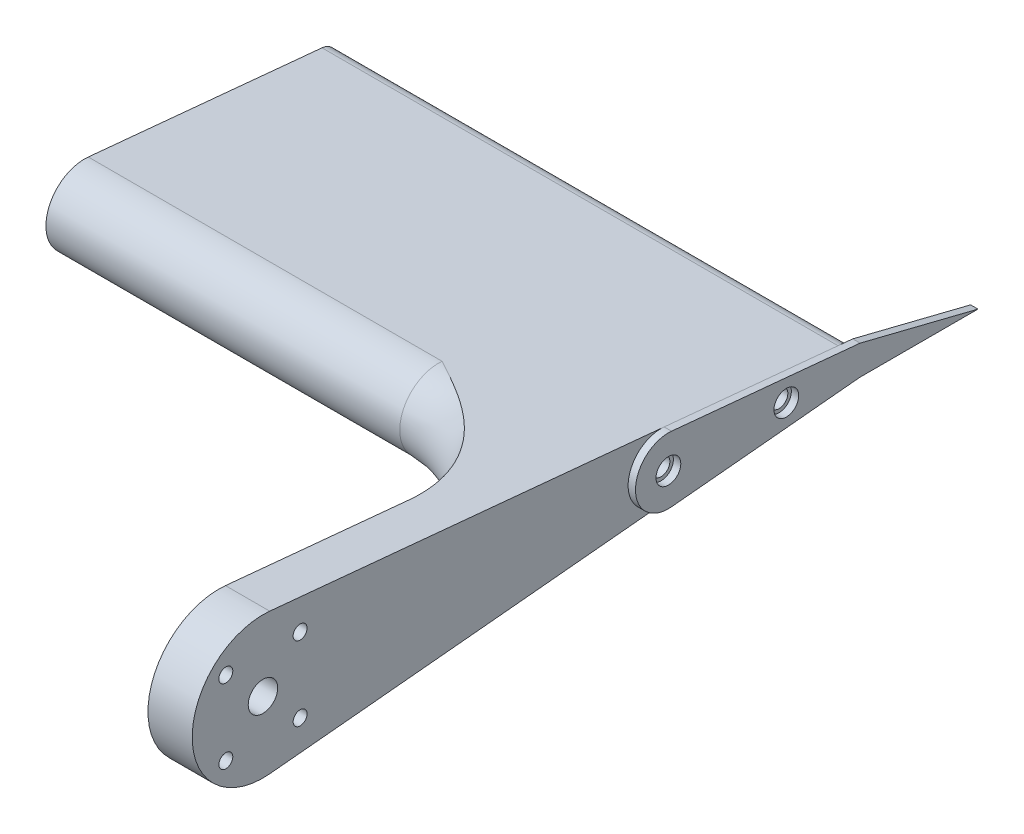
SolidWorks part; units mm, degrees
material "PLA/ABS"
ref_plane "Front Plane" through (0, 0, 0) normal (0, 0, 1) x (1, 0, 0)
ref_plane "Top Plane" through (0, 0, 0) normal (0, 1, 0) x (1, 0, 0)
ref_plane "Right Plane" through (0, 0, 0) normal (1, 0, 0) x (0, 0, -1)
other "Bounding Box"
ref_plane "Default Plane" through (-8.9266, -12.7485, 0) normal (-0.1736, 0.9848, 0) x (0.9848, 0.1736, 0)
sketch "Sketch1" plane through (0, 0, 0) normal (1, 0, 0) x (0, 0, -1)
  line L0 (1.4495, 15.1709) -> (123.8394, 3.477)
  line L1 (-8, 8) -> (8, 8) construction
  line L2 (-8, 8) -> (-8, -8) construction
  line L3 (-8, -8) -> (8, -8) construction
  line L4 (8, 8) -> (8, -8) construction
  line L5 (-8, 8) -> (8, -8) construction
  line L6 (-8, -8) -> (8, 8) construction
  line L7 (1.4495, -15.1709) -> (123.8394, -3.477)
  line L8 (0, 0) -> (152.4, 0) construction
  line L11 (127, -3.175) -> (127, 3.175) construction
  line L12 (127, 3.175) -> (152.4, -3.175) construction
  line L13 (152.4, -3.175) -> (127, -3.175) construction
  line L14 (152.4, -3.175) -> (152.4, 0) construction
  line L15 (123.8394, -3.477) -> (127, -3.175) construction
  line L16 (123.8394, 3.477) -> (127, 3.175) construction
  circle A0 centre (0, 0) radius 3.175
  circle A1 centre (-8, 8) radius 1.5
  circle A2 centre (8, 8) radius 1.5
  circle A3 centre (8, -8) radius 1.5
  circle A4 centre (-8, -8) radius 1.5
  arc A5 (1.4495, 15.1709) -> (1.4495, -15.1709) centre (0, 0) ccw
  arc A8 (123.8394, 3.477) -> (123.8394, -3.477) centre (123.5072, 0) cw
  point P13 (127, 0)
  point P20 (127, 0)
  point P22 (127, 0)
  dimension "D2" = 3
  dimension "D3" = 6.35
  dimension "D10" = 15.24
  dimension "D1" = 16
  dimension "D4" = 152.4
  dimension "D5" = 6.35
  dimension "D6" = 25.4
extrude "Boss-Extrude1" add sketch "Sketch1" along normal mid plane 9.525
sketch "Sketch3" plane through (-4.7625, 0, 0) normal (-1, 0, 0) x (0, 0, 1)
  line L0 (-123.8394, 3.477) -> (-1.4495, 15.1709) construction
  line L1 (-123.5072, 0) -> (-72.7072, 0) construction
  line L2 (-1.4495, 15.1709) -> (-123.8394, 3.477)
  line L3 (-123.8394, -3.477) -> (-1.4495, -15.1709)
  line L4 (-73.499, 8.2868) -> (-123.8394, 3.477)
  line L5 (-123.8394, -3.477) -> (-73.499, -8.2868)
  arc A0 (-73.499, 8.2868) -> (-73.499, -8.2868) centre (-72.7072, 0) cw
  arc A2 (-1.4495, -15.1709) -> (-1.4495, 15.1709) centre (0, 0) ccw
  arc A3 (-123.8394, 3.477) -> (-123.8394, -3.477) centre (-123.5072, 0) ccw
  arc A5 (-123.8394, 3.477) -> (-123.8394, -3.477) centre (-123.5072, 0) ccw
  point P5 (-65.2565, 9.0744)
  dimension "D2" = 50.8
  dimension "D1" = 0
extrude "Boss-Extrude2" add sketch "Sketch3" along normal blind 101.6
sketch "Sketch4" plane through (4.7625, 0, 0) normal (1, 0, 0) x (0, 0, -1)
  line L0 (0, 0) -> (152.4, 0) construction
  line L1 (1.4495, -15.1709) -> (123.8394, -3.477) construction
  line L2 (1.4495, 15.1709) -> (123.8394, 3.477) construction
  line L3 (127, 3.175) -> (152.4, -3.175) construction
  line L4 (152.4, -3.175) -> (127, -3.175) construction
  line L5 (127, 3.175) -> (152.4, -3.175)
  line L6 (152.4, -3.175) -> (127, -3.175)
  line L7 (86.399, 7.0543) -> (127, 3.175)
  line L8 (127, -3.175) -> (86.399, -7.0543)
  arc A0 (86.399, -7.0543) -> (86.399, 7.0543) centre (85.725, 0) cw
  circle A1 centre (111.125, 0) radius 2.667
  circle A2 centre (85.725, 0) radius 2.667
  dimension "D1" = 5.334
  dimension "D2" = 25.4
  dimension "D3" = 41.275
extrude "Boss-Extrude3" add sketch "Sketch4" along normal blind 1.5875 separate body
sketch "Sketch5" plane through (4.7625, 0, 0) normal (1, 0, 0) x (0, 0, -1)
  circle A0 centre (85.725, 0) radius 1.905
  circle A1 centre (111.125, 0) radius 1.905
  dimension "D1" = 3.81
extrude "Cut-Extrude1" cut sketch "Sketch5" against normal blind 25.4
fillet "Fillet1" radius 25.4 1 edges at (-4.7625, 0, -64.3826)
